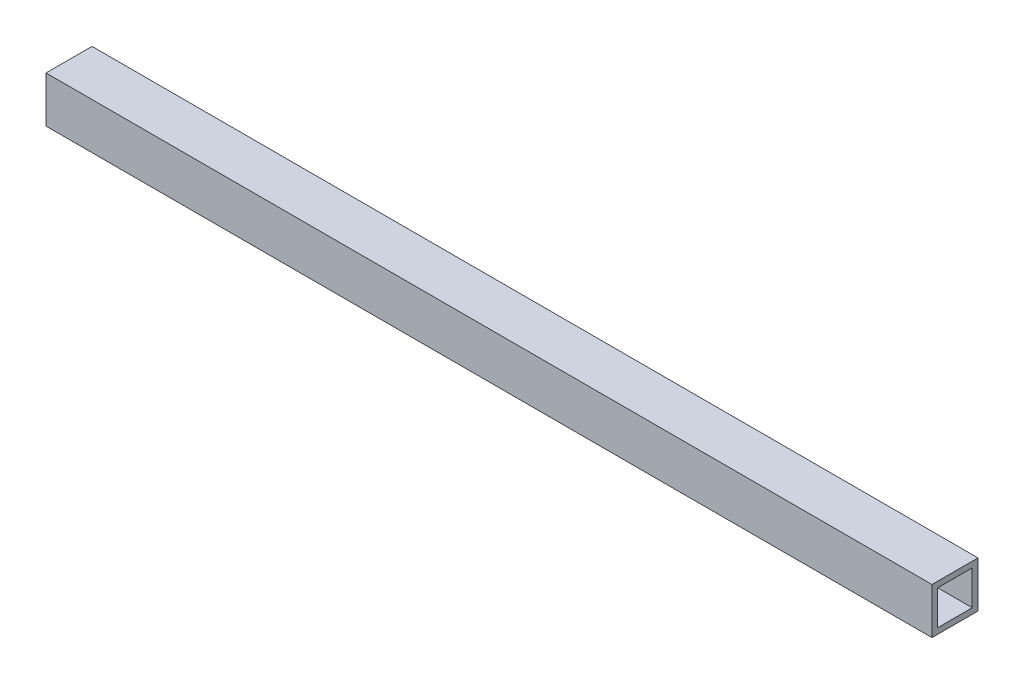
SolidWorks part; units mm, degrees
material "PC High Viscosity"
ref_plane "Front Plane" through (0, 0, 0) normal (0, 0, 1) x (1, 0, 0)
ref_plane "Top Plane" through (0, 0, 0) normal (0, 1, 0) x (1, 0, 0)
ref_plane "Right Plane" through (0, 0, 0) normal (1, 0, 0) x (0, 0, -1)
sketch "Sketch1" plane through (0, 0, 0) normal (1, 0, 0) x (0, 0, -1)
  line L0 (12.7, 12.7) -> (-12.7, 12.7)
  line L1 (9.525, -9.525) -> (-9.525, -9.525)
  line L2 (9.525, -9.525) -> (9.525, 9.525)
  line L3 (9.525, 9.525) -> (-9.525, 9.525)
  line L4 (-9.525, -9.525) -> (-9.525, 9.525)
  line L5 (9.525, -9.525) -> (-9.525, 9.525) construction
  line L6 (9.525, 9.525) -> (-9.525, -9.525) construction
  line L7 (-12.7, -12.7) -> (-12.7, 12.7)
  line L8 (12.7, -12.7) -> (-12.7, -12.7)
  line L9 (12.7, -12.7) -> (12.7, 12.7)
  point P0 (0, 0)
  dimension "D1" = 3.175
  dimension "D2" = 25.4
extrude "Boss-Extrude1" add sketch "Sketch1" along normal mid plane 488.95
